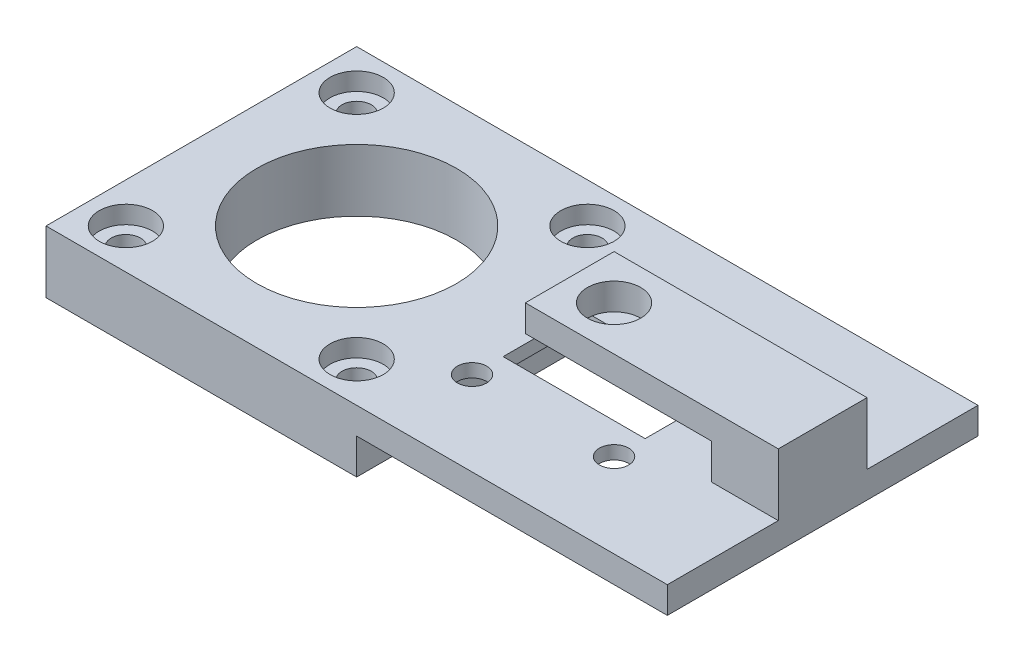
SolidWorks part; units mm, degrees
ref_plane "Front Plane" through (0, 0, 0) normal (0, 0, 1) x (1, 0, 0)
ref_plane "Top Plane" through (0, 0, 0) normal (0, 1, 0) x (1, 0, 0)
ref_plane "Right Plane" through (0, 0, 0) normal (1, 0, 0) x (0, 0, -1)
sketch "Sketch1" plane through (0, 0, 0) normal (0, 1, 0) x (1, 0, 0)
  line L1 (-35, -17.5) -> (35, -17.5)
  line L2 (-35, -17.5) -> (-35, 17.5)
  line L3 (-35, 17.5) -> (35, 17.5)
  line L4 (35, -17.5) -> (35, 17.5)
  line L5 (-35, -17.5) -> (35, 17.5) construction
  line L6 (-35, 17.5) -> (35, -17.5) construction
  point P0 (0, 0)
  dimension "D1" = 70
  dimension "D2" = 35
extrude "Boss-Extrude1" add sketch "Sketch1" along normal blind 3
sketch "Sketch3" plane through (0, 3, 0) normal (0, 1, 0) x (1, 0, 0)
  line L0 (-35, -17.5) -> (35, -17.5) construction
  line L1 (-35, 17.5) -> (0, 17.5)
  line L2 (-35, 17.5) -> (-35, -17.5)
  line L3 (-35, -17.5) -> (0, -17.5)
  line L4 (0, 17.5) -> (0, -17.5)
  dimension "D1" = 35
extrude "Boss-Extrude2" add sketch "Sketch3" against normal blind 4 from offset 3 offset against normal yes
sketch "Sketch2" plane through (0, 3, 0) normal (0, 1, 0) x (1, 0, 0)
  line L0 (-35, 0) -> (35, 0) construction
  line L1 (-35, 17.5) -> (-35, -17.5) construction
  line L2 (35, -17.5) -> (35, 17.5) construction
  line L3 (-17.5, 17.5) -> (-17.5, -17.5) construction
  line L4 (35, 17.5) -> (-35, 17.5) construction
  line L5 (-35, -17.5) -> (35, -17.5) construction
  circle A0 centre (-30.5, 13) radius 1.65
  circle A1 centre (-4.5, 13) radius 1.65
  circle A2 centre (-4.5, -13) radius 1.65
  circle A3 centre (-30.5, -13) radius 1.65
  circle A4 centre (-17.5, 0) radius 11.25
  dimension "D2" = 3.3
  dimension "D3" = 13
  dimension "D4" = 13
  dimension "D5" = 22.5
  dimension "D1" = 17.5
extrude "Cut-Extrude1" cut sketch "Sketch2" against normal through all both and the other way through all
sketch "Sketch5" plane through (0, 3, 0) normal (0, 1, 0) x (1, 0, 0)
  line L0 (0, 0) -> (-35, 0) construction
  line L1 (-35, 17.5) -> (-35, -17.5) construction
  line L2 (-17.5, 0) -> (-17.5, 17.5) construction
  line L3 (35, 17.5) -> (-35, 17.5) construction
  circle A0 centre (-30.5, 13) radius 3
  circle A1 centre (-4.5, 13) radius 3
  circle A2 centre (-4.5, -13) radius 3
  circle A3 centre (-30.5, -13) radius 3
  dimension "D1" = 6
extrude "Cut-Extrude3" cut sketch "Sketch5" against normal blind 2
sketch "Sketch6" plane through (0, 0, 0) normal (0, -1, 0) x (1, 0, 0)
  line L0 (0, 0) -> (23, 0) construction
  line L1 (23, 0) -> (23, 11.5) construction
  line L2 (23, 11.5) -> (0, 11.5) construction
  line L3 (0, 17.5) -> (0, -17.5) construction
  line L4 (11.5, 11.5) -> (11.5, 0) construction
  line L6 (3.5, -4.5) -> (19.5, -4.5)
  line L7 (3.5, -4.5) -> (3.5, 4.5)
  line L8 (3.5, 4.5) -> (19.5, 4.5)
  line L9 (19.5, -4.5) -> (19.5, 4.5)
  line L10 (3.5, -4.5) -> (19.5, 4.5) construction
  line L11 (3.5, 4.5) -> (19.5, -4.5) construction
  circle A0 centre (3.5, 8) radius 1.65
  circle A1 centre (19.5, 8) radius 1.65
  circle A2 centre (19.5, -8) radius 1.65
  circle A3 centre (3.5, -8) radius 1.65
  dimension "D3" = 3.3
  dimension "D4" = 8
  dimension "D5" = 8
  dimension "D1" = 23
  dimension "D2" = 11.5
  dimension "D6" = 16
  dimension "D7" = 9
extrude "Cut-Extrude4" cut sketch "Sketch6" against normal through all
sketch "Sketch7" plane through (0, 0, 0) normal (0, -1, 0) x (-1, 0, 0)
  line L0 (0, 0) -> (0, -12) construction
  line L1 (0, -17.5) -> (0, 17.5) construction
  line L2 (0, -12) -> (-24, -12) construction
  line L4 (-24, -12) -> (0, -12)
  line L5 (-24, -12) -> (-24, 12)
  line L6 (-24, 12) -> (0, 12)
  line L7 (0, -12) -> (0, 12)
  dimension "D1" = 12
  dimension "D2" = 24
  dimension "D3" = 24
extrude "Cut-Extrude5" cut sketch "Sketch7" against normal blind 1.5
sketch "Sketch8" plane through (0, 3, 0) normal (0, 1, 0) x (1, 0, 0)
  line L0 (35, 0) -> (31.25, 0) construction
  line L1 (35, -17.5) -> (35, 17.5) construction
  line L3 (27.5, -5) -> (35, -5)
  line L4 (27.5, -5) -> (27.5, 5)
  line L5 (27.5, 5) -> (35, 5)
  line L6 (35, -5) -> (35, 5)
  line L7 (27.5, -5) -> (35, 5) construction
  line L8 (27.5, 5) -> (35, -5) construction
  dimension "D1" = 10
  dimension "D2" = 7.5
extrude "Boss-Extrude3" add sketch "Sketch8" along normal blind 7
sketch "Sketch9" plane through (27.5, 0, 0) normal (-1, 0, 0) x (0, 0, 1)
  line L0 (5, 10) -> (5, 3) construction
  line L1 (-5, 10) -> (5, 10)
  line L2 (-5, 10) -> (-5, 7)
  line L3 (-5, 7) -> (5, 7)
  line L4 (5, 10) -> (5, 7)
  dimension "D1" = 3
extrude "Boss-Extrude4" add sketch "Sketch9" along normal blind 21
sketch "Sketch10" plane through (0, 10, 0) normal (0, 1, 0) x (1, 0, 0)
  line L0 (6.5, 0) -> (35, 0) construction
  line L1 (6.5, -5) -> (6.5, 5) construction
  line L2 (35, -5) -> (35, 5) construction
  circle A0 centre (11.5, 0) radius 3
  dimension "D1" = 6
  dimension "D2" = 5
extrude "Cut-Extrude6" cut sketch "Sketch10" against normal up to next
